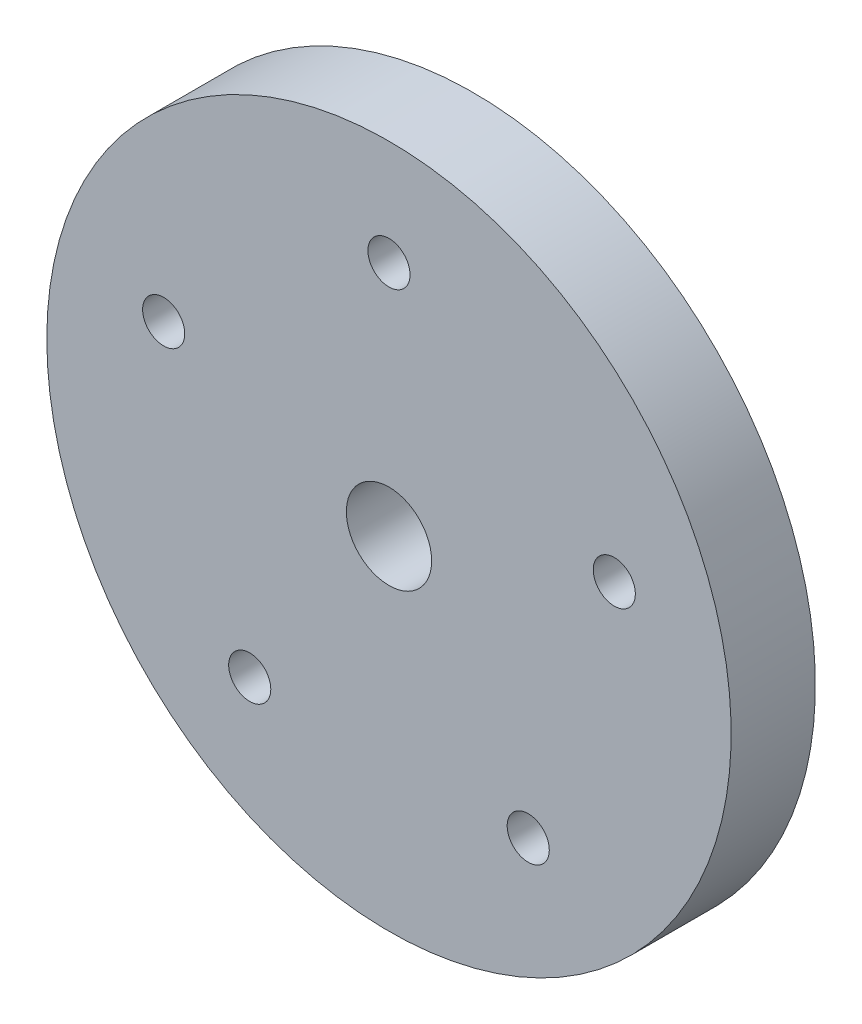
SolidWorks part; units mm, degrees
ref_plane "Ebene vorne" through (0, 0, 0) normal (0, 0, 1) x (1, 0, 0)
ref_plane "Ebene oben" through (0, 0, 0) normal (0, 1, 0) x (1, 0, 0)
ref_plane "Ebene rechts" through (0, 0, 0) normal (1, 0, 0) x (0, 0, -1)
sketch "Skizze1" plane through (0, 0, 0) normal (1, 0, 0) x (0, 0, -1)
  line L0 (0, 0) -> (0, -44862.1348) construction
  line L1 (0, 0) -> (-44862.1348, 0) construction
  line L2 (0, 0) -> (20, 0)
  line L3 (20, 0) -> (20, 15)
  line L4 (20, 15) -> (8, 15)
  line L5 (8, 15) -> (8, 32.5)
  line L6 (8, 32.5) -> (0, 32.5)
  line L7 (0, 32.5) -> (0, 0)
  dimension "D1" = 30
  dimension "D2" = 65
  dimension "D3" = 20
  dimension "D4" = 12
revolve "Rotation1" add sketch "Skizze1" angle 360 about L1
hole_wizard "Ø4.0 (4) Heat Insert M3" positions "Skizze2" profile "Skizze3" hole size "Ø4.0" standard "ISO" end condition through all
sketch "Skizze2" plane through (0, 0, 0) normal (0, 0, 1) x (1, 0, 0)
  circle A0 centre (0, 0) radius 22.5 construction
  point P7 (0, 22.5)
  dimension "D1" = 45
sketch "Skizze3" plane through (0, 22.5, 0) normal (1, 0, 0) x (0, -1, 0)
  line L0 (0, 0) -> (0, 20)
  line L1 (0, 20) -> (2, 20)
  line L2 (2, 20) -> (2, 0)
  line L5 (2, 0) -> (0, 0)
  line L11 (0, -6.35) -> (0, 107.95) construction
  dimension "Bohrerdurchmesser" = 4
  dimension "Bohrungstiefe" = 20
hole_wizard "Ø8.1 (8.1) Durchmesser Bohrung1" positions "Skizze4" profile "Skizze5" hole size "Ø8.1" standard "ISO" end condition through all
sketch "Skizze4" plane through (0, 0, 0) normal (0, 0, 1) x (1, 0, 0)
  point P0 (0, 0)
sketch "Skizze5" plane through (0, 0, 0) normal (1, 0, 0) x (0, -1, 0)
  line L0 (0, 0) -> (0, 20)
  line L1 (0, 20) -> (4.05, 20)
  line L2 (4.05, 20) -> (4.05, 0)
  line L5 (4.05, 0) -> (0, 0)
  line L11 (0, -6.35) -> (0, 107.95) construction
  dimension "Bohrerdurchmesser" = 8.1
  dimension "Bohrungstiefe" = 20
sketch "Skizze8" plane through (0, 0, -20) normal (0, 0, -1) x (-1, 0, 0)
  line L0 (0, 0) -> (0, 50000) construction
  circle A0 centre (0, 0) radius 10 construction
  circle A1 centre (0, 10) radius 1.2
  circle A2 centre (8.6603, -5) radius 1.2
  circle A3 centre (-8.6603, -5) radius 1.2
  point P14 (0, 0)
  dimension "D1" = 20
  dimension "D2" = 2.4
  dimension "D3" = 3
extrude "Schnitt-Linear austragen1" cut sketch "Skizze8" against normal blind 7
pattern_circular "Kreismuster1" count 5 over 360 about axis through (0, 0, 0) along (0, 0, 1) of "Ø4.0 (4) Heat Insert M3"
